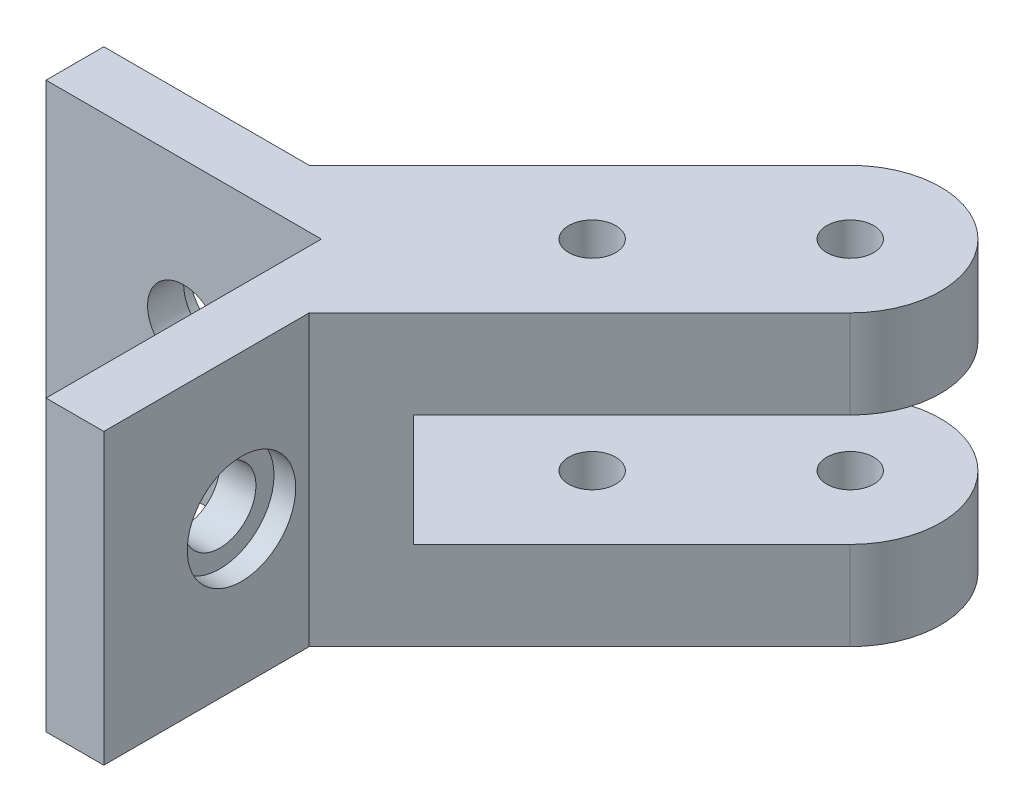
SolidWorks part; units mm, degrees
ref_plane "Front Plane" through (0, 0, 0) normal (0, 0, 1) x (1, 0, 0)
ref_plane "Top Plane" through (0, 0, 0) normal (0, 1, 0) x (1, 0, 0)
ref_plane "Right Plane" through (0, 0, 0) normal (1, 0, 0) x (0, 0, -1)
sketch "Sketch2" plane through (0, 0, 0) normal (0, 1, 0) x (1, 0, 0)
  line L0 (0, 35.2326) -> (0, -59.4419) construction
  line L1 (-78.3628, 0) -> (43.3721, 0) construction
  line L2 (-38.1, 0) -> (-38.1, 8)
  line L3 (-38.1, 8) -> (-9.6777, 8)
  line L4 (8, -9.6777) -> (8, -38.1)
  line L5 (8, -38.1) -> (0, -38.1)
  line L6 (0, -38.1) -> (0, 0)
  line L7 (0, 0) -> (-38.1, 0)
  line L8 (0, 0) -> (60.1953, 60.1953) construction
  line L9 (-9.6777, 8) -> (27.7539, 45.4316)
  line L11 (8, -9.6777) -> (45.4316, 27.7539)
  arc A0 (45.4316, 27.7539) -> (27.7539, 45.4316) centre (36.5928, 36.5928) ccw
  circle A1 centre (18.7383, 18.7383) radius 3.25
  circle A2 centre (36.5928, 36.5928) radius 3.25
  dimension "D7" = 25
  dimension "D8" = 51.75
  dimension "D9" = 6.5
  dimension "D10" = 26.5
  dimension "D11" = 6.5
  dimension "D1" = 8
  dimension "D2" = 8
  dimension "D3" = 38.1
  dimension "D4" = 38.1
  dimension "D5" = 45
  dimension "D6" = 12.5
extrude "Boss-Extrude1" add sketch "Sketch2" along normal blind 40
ref_plane "Plane1" through (0, 0, 0) normal (0.7071, 0, 0.7071) x (0, -1, 0)
sketch "Sketch3" plane through (0, 0, 0) normal (0.7071, 0, 0.7071) x (0, -1, 0)
  line L0 (-20, 91.1467) -> (-20, -35.741) construction
  line L1 (-82.5199, 0) -> (41.5014, 0) construction
  line L2 (-82.5199, 9) -> (41.5014, 9) construction
  line L4 (-12.25, 9) -> (-27.75, 9)
  line L5 (-12.25, 9) -> (-12.25, 69)
  line L7 (-27.75, 9) -> (-27.75, 69)
  line L8 (-35, 89) -> (-35, 69)
  line L9 (-35, 69) -> (-27.75, 69)
  line L10 (-5, 69) -> (-12.25, 69)
  line L11 (-5, 89) -> (-5, 69)
  line L13 (-35, 89) -> (-5, 89)
  dimension "D1" = 9
  dimension "D2" = 20
  dimension "D3" = 30
  dimension "D4" = 7.75
  dimension "D5" = 80
  dimension "D6" = 20
extrude "Cut-Extrude1" cut sketch "Sketch3" against normal through all both and the other way through all
sketch "Sketch4" plane through (0, 0, 0) normal (0, 0, 1) x (1, 0, 0)
  line L0 (-40.6639, 20) -> (24.2822, 20) construction
  circle A0 centre (-19.05, 20) radius 5
  dimension "D1" = 19.05
  dimension "D2" = 10
  dimension "D3" = 20
extrude "Cut-Extrude2" cut sketch "Sketch4" against normal blind 50
sketch "Sketch5" plane through (0, 0, -8) normal (0, 0, -1) x (-1, 0, 0)
  circle A0 centre (19.05, 20) radius 7.5
  dimension "D1" = 15
sketch "Sketch6" plane through (0, 0, 0) normal (-1, 0, 0) x (0, 0, 1)
  line L0 (44.8405, 20) -> (-19.2703, 20) construction
  circle A0 centre (19.05, 20) radius 5
  dimension "D1" = 10
  dimension "D2" = 19.05
  dimension "D3" = 20
extrude "Cut-Extrude4" cut sketch "Sketch6" against normal blind 50
sketch "Sketch7" plane through (8, 0, 0) normal (1, 0, 0) x (0, 0, -1)
  circle A0 centre (-19.05, 20) radius 7.5
  dimension "D1" = 15
extrude "Cut-Extrude5" cut sketch "Sketch7" against normal blind 3
sketch "Sketch8" plane through (0, 12.25, 0) normal (0, 1, 0) x (1, 0, 0)
  circle A0 centre (18.7383, 18.7383) radius 5
  circle A1 centre (18.7383, 18.7383) radius 3.25
  dimension "D1" = 10
sketch "Sketch9" plane through (0, 27.75, 0) normal (0, -1, 0) x (1, 0, 0)
  circle A0 centre (18.7383, -18.7383) radius 5
  circle A1 centre (18.7383, -18.7383) radius 3.25
  dimension "D1" = 10
  dimension "D2" = 6.5
ref_plane "Plane2" through (0, 0, 0) normal (0, 1, 0) x (1, 0, 0)
sketch "Sketch10" plane through (0, 0, 0) normal (0, 1, 0) x (1, 0, 0)
  line L0 (-48.6924, 0) -> (48.6032, 0) construction
  line L1 (0, 0) -> (87.0071, 87.0071) construction
  line L2 (18.7383, 18.7383) -> (40.5375, -3.0609) construction
  line L3 (18.7383, 18.7383) -> (-25.3652, 62.8419) construction
  line L17 (14.5742, 22.9025) -> (13.05, 17.2142)
  line L18 (13.05, 17.2142) -> (17.2142, 13.05)
  line L19 (17.2142, 13.05) -> (22.9025, 14.5742)
  line L20 (22.9025, 14.5742) -> (24.4266, 20.2625)
  line L21 (24.4266, 20.2625) -> (20.2625, 24.4266)
  line L22 (20.2625, 24.4266) -> (14.5742, 22.9025)
  line L23 (35.0686, 30.9045) -> (40.7569, 32.4286)
  line L24 (40.7569, 32.4286) -> (42.2811, 38.117)
  line L25 (42.2811, 38.117) -> (38.117, 42.2811)
  line L26 (38.117, 42.2811) -> (32.4286, 40.7569)
  line L27 (32.4286, 40.7569) -> (30.9045, 35.0686)
  line L28 (30.9045, 35.0686) -> (35.0686, 30.9045)
  circle A0 centre (36.5928, 36.5928) radius 5.1 construction
  circle A1 centre (18.7383, 18.7383) radius 5.1 construction
  point P16 (32.7388, 4.7378)
  point P17 (14.6725, 22.8042)
  dimension "D1" = 5.1
  dimension "D2" = 45
  dimension "D3" = 5.1
extrude "Cut-Extrude6" cut sketch "Sketch10" along normal blind 5.1
extrude "Cut-Extrude7" cut sketch "Sketch5" against normal blind 3
sketch "Sketch11" plane through (0, 12.25, 0) normal (0, 1, 0) x (1, 0, 0)
  circle A0 centre (18.7383, 18.7383) radius 12.5
  dimension "D1" = 25
